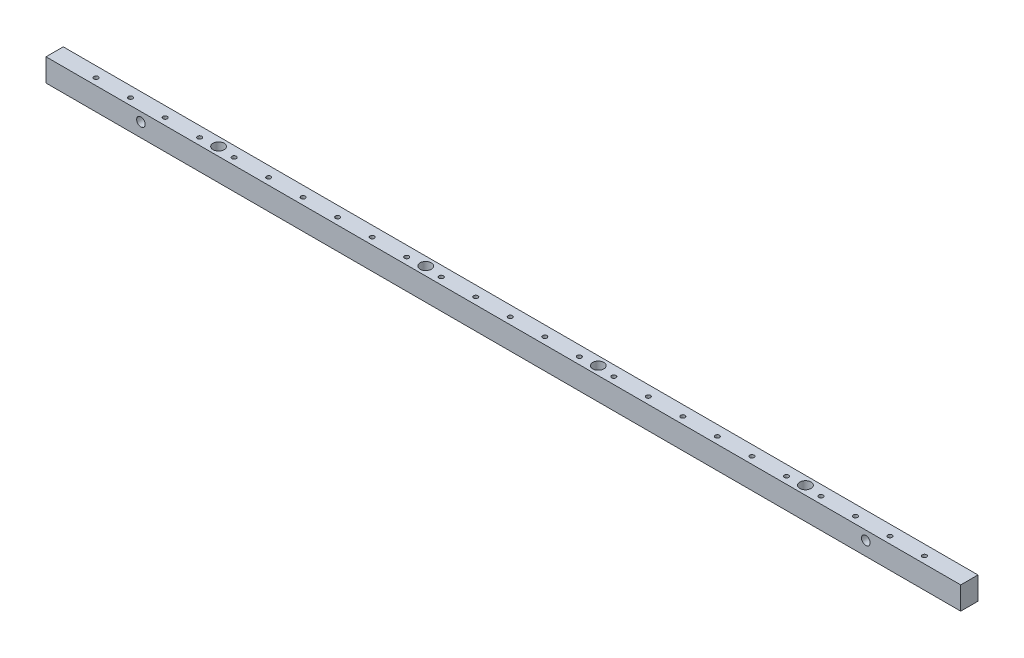
SolidWorks part; units mm, degrees
ref_plane "Front Plane" through (0, 0, 0) normal (0, 0, 1) x (1, 0, 0)
ref_plane "Top Plane" through (0, 0, 0) normal (0, 1, 0) x (1, 0, 0)
ref_plane "Right Plane" through (0, 0, 0) normal (1, 0, 0) x (0, 0, -1)
sketch "Sketch1" plane through (0, 0, 0) normal (0, 1, 0) x (1, 0, 0)
  line L1 (265, -5) -> (-265, -5)
  line L2 (265, -5) -> (265, 5)
  line L3 (265, 5) -> (-265, 5)
  line L4 (-265, -5) -> (-265, 5)
  line L5 (265, -5) -> (-265, 5) construction
  line L6 (265, 5) -> (-265, -5) construction
  point P0 (0, 0)
  dimension "D1" = 530
  dimension "D2" = 10
extrude "Boss-Extrude1" add sketch "Sketch1" along normal blind 13.2
sketch "Sketch2" plane through (0, 13.2, 0) normal (0, 1, 0) x (1, 0, 0)
  line L0 (-265, -1) -> (265, -1) construction
  line L1 (-265, 5) -> (-265, -5) construction
  line L2 (265, -5) -> (265, 5) construction
  line L3 (-265, -5) -> (265, -5) construction
  point P8 (0, -1)
  point P9 (0, 0)
  point P11 (0, -1)
  dimension "D1" = 4
hole_wizard "M3x0.5 Tapped Hole1" positions "3DSketch1" profile "Sketch4" tap size "M3x0.5" standard "BSI" end condition through all
sketch3d "3DSketch1"
  point P0 (0, 13.2, 1)
sketch "Sketch4" plane through (0, 13.2, 1) normal (1, 0, 0) x (0, 0, 1)
  line L0 (0, 0) -> (0, 13.2)
  line L1 (0, 13.2) -> (1.25, 13.2)
  line L2 (1.25, 13.2) -> (1.25, 0)
  line L5 (1.25, 0) -> (0, 0)
  line L11 (0, -6.35) -> (0, 107.95) construction
  dimension "Thru Tap Drill Dia." = 2.5
  dimension "Thru Tap Drill Depth" = 13.2
cosmetic thread "Hole Thread1" parameters "D2"=3
pattern_linear "LPattern1" count 13 spacing 20 along (1, 0, 0) count 13 spacing 20 along (-1, 0, 0) of "M3x0.5 Tapped Hole1"
sketch "Sketch5" plane through (0, 0, 5) normal (0, 0, 1) x (1, 0, 0)
  line L0 (265, 8) -> (210, 8) construction
  line L2 (265, 13.2) -> (265, 0) construction
  line L3 (-265, 0) -> (265, 0) construction
  point P2 (265, 7.7781)
  point P5 (210, 8)
  dimension "D1" = 55
  dimension "D2" = 8
hole_wizard "M6x1.0 Tapped Hole1" positions "3DSketch2" profile "Sketch6" tap size "M6x1.0" standard "BSI"
sketch3d "3DSketch2"
  point P0 (210, 8, 5)
sketch "Sketch6" plane through (210, 8, 5) normal (1, 0, 0) x (0, -1, 0)
  line L0 (0, 0) -> (0, 16.5022)
  line L1 (0, 16.5022) -> (2.5, 15)
  line L2 (2.5, 15) -> (2.5, 0)
  line L5 (2.5, 0) -> (0, 0)
  line L10 (0, 16.5022) -> (-2.5, 15) construction
  line L11 (0, -6.35) -> (0, 107.95) construction
  dimension "Tap Drill Dia." = 5
  dimension "Tap Drill Depth" = 15
  dimension "Drill Angle" = 118
cosmetic thread "Hole Thread2" parameters "D1"=10, "D2"=6
sketch "Sketch7" plane through (0, 13.2, 0) normal (0, 1, 0) x (1, 0, 0)
  line L0 (-265, 0) -> (265, 0) construction
  line L1 (-265, 5) -> (-265, -5) construction
  line L2 (265, -5) -> (265, 5) construction
  point P6 (-170, 0)
  point P7 (-50, 0)
  point P8 (50, 0)
  point P9 (170, 0)
  dimension "D1" = 50
  dimension "D2" = 170
  dimension "D3" = 50
  dimension "D4" = 170
hole_wizard "CBORE for M3 SHCS1" positions "3DSketch3" profile "Sketch9" counterbore size "M3" standard "ANSI Metric"
sketch3d "3DSketch3"
  line L0 (-265, 13.2, 0) -> (265, 13.2, 0) construction
  point P0 (-170, 13.2, 0)
  point P3 (-50, 13.2, 0)
  point P6 (50, 13.2, 0)
  point P9 (170, 13.2, 0)
  point P13 (172.1028, 15, 0)
sketch "Sketch9" plane through (-170, 13.2, 0) normal (1, 0, 0) x (0, 0, 1)
  line L0 (0, 0) -> (0, 16.0815)
  line L1 (0, 16.0815) -> (1.8, 15)
  line L2 (1.8, 15) -> (1.8, 5)
  line L3 (1.8, 5) -> (3.25, 5)
  line L4 (3.25, 5) -> (3.25, 0)
  line L5 (3.25, 0) -> (0, 0)
  line L10 (0, 16.0815) -> (-1.8, 15) construction
  line L11 (0, -6.35) -> (0, 107.95) construction
  dimension "Hole Dia." = 3.6
  dimension "Hole Depth" = 15
  dimension "C'Bore Dia." = 6.5
  dimension "C'Bore Depth" = 5
  dimension "Drill Angle" = 118
mirror "Mirror1" about plane through (0, 0, 0) normal (1, 0, 0) of "M6x1.0 Tapped Hole1"
equation "\"D3@Sketch7\"=\"D1@Sketch7\""
equation "\"D4@Sketch7\"=\"D2@Sketch7\""
